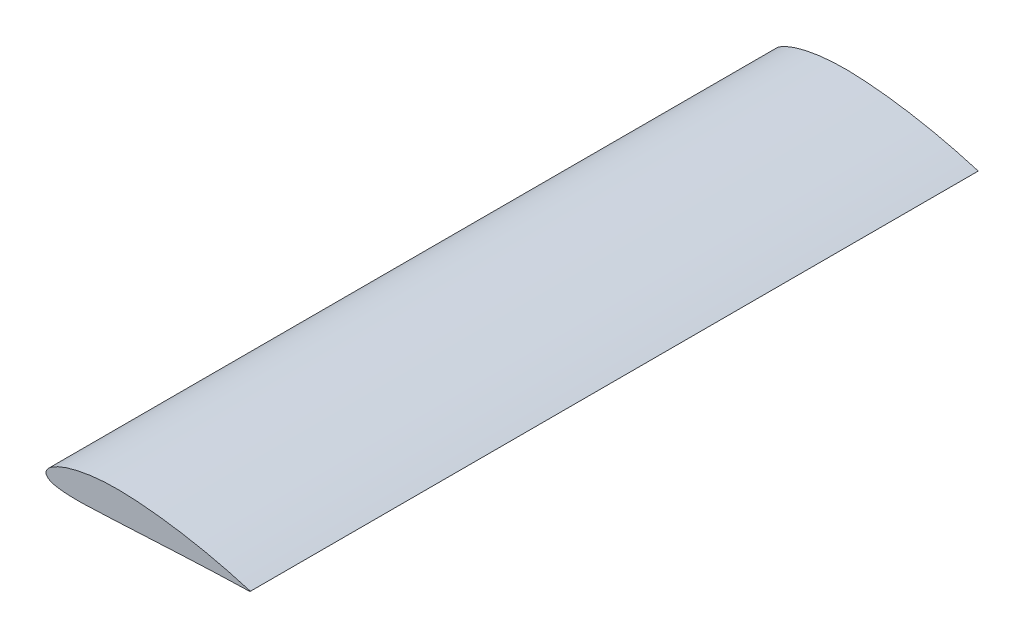
SolidWorks part; units mm, degrees
ref_plane "Front Plane" through (0, 0, 0) normal (1, 0, 0) x (0, 1, 0)
ref_plane "Top Plane" through (0, 0, 0) normal (0, 0, 1) x (0, 1, 0)
ref_plane "Right Plane" through (0, 0, 0) normal (0, 1, 0) x (-1, 0, 0)
curve "Curve1"
  spline degree 3 poles (140.0272, 0.204, 0) (139.9568, 0.2252, 0) (139.6757, 0.3101, 0) (139.0445, 0.4996, 0) (137.9962, 0.8116, 0) (136.5364, 1.24, 0) (134.6729, 1.777, 0) (132.4156, 2.4129, 0) (129.7768, 3.1359, 0) (126.7711, 3.9337, 0) (123.4152, 4.7928, 0) (119.7281, 5.6984, 0) (115.7307, 6.6363, 0) (111.4464, 7.5912, 0) (106.9, 8.5481, 0) (102.1186, 9.4924, 0) (97.1306, 10.4094, 0) (91.9664, 11.285, 0) (86.6574, 12.105, 0) (81.2364, 12.857, 0) (75.7371, 13.5278, 0) (70.1942, 14.1063, 0) (64.643, 14.582, 0) (59.1045, 14.945, 0) (53.595, 15.1934, 0) (48.1487, 15.2539, 0) (42.8195, 15.1314, 0) (37.6645, 14.8278, 0) (32.721, 14.3506, 0) (28.0244, 13.7113, 0) (23.608, 12.9241, 0) (19.5026, 12.0063, 0) (15.7359, 10.9777, 0) (12.3325, 9.8591, 0) (9.3132, 8.6734, 0) (6.6949, 7.4424, 0) (4.4906, 6.1877, 0) (2.7084, 4.928, 0) (1.3523, 3.6768, 0) (0.4223, 2.4391, 0) (-0.0704, 1.2019, 0) (-0.0774, -0.0155, 0) (0.3962, -1.1349, 0) (1.3132, -2.0898, 0) (2.6166, -2.8909, 0) (4.297, -3.5632, 0) (6.348, -4.1161, 0) (8.7591, -4.5545, 0) (11.516, -4.8827, 0) (14.6016, -5.1058, 0) (17.9973, -5.2305, 0) (21.6831, -5.2648, 0) (25.6381, -5.2189, 0) (29.8408, -5.1042, 0) (34.2692, -4.9332, 0) (38.9005, -4.7202, 0) (43.7112, -4.4799, 0) (48.6771, -4.2275, 0) (53.7919, -3.9752, 0) (59.0436, -3.7443, 0) (64.3998, -3.4808, 0) (69.8109, -3.2013, 0) (75.2301, -2.9143, 0) (80.6252, -2.6276, 0) (85.9637, -2.348, 0) (91.213, -2.0804, 0) (96.3409, -1.8293, 0) (101.3154, -1.5967, 0) (106.1052, -1.3844, 0) (110.68, -1.1929, 0) (115.0103, -1.0216, 0) (119.0681, -0.87, 0) (122.827, -0.7367, 0) (126.2621, -0.6209, 0) (129.3505, -0.521, 0) (132.0713, -0.4363, 0) (134.4061, -0.3656, 0) (136.3389, -0.3086, 0) (137.8565, -0.2644, 0) (138.948, -0.2331, 0) (139.6061, -0.2145, 0) (139.8994, -0.2061, 0) (139.9728, -0.204, 0) knots 0 0 0 0 0.000765 0.003057 0.00686 0.012149 0.018893 0.027046 0.036559 0.047372 0.059416 0.072616 0.086892 0.102153 0.118305 0.13525 0.152883 0.171093 0.18977 0.208797 0.228058 0.247433 0.266803 0.286048 0.305204 0.324202 0.342731 0.360679 0.377941 0.394414 0.410004 0.424621 0.438187 0.450631 0.461894 0.471932 0.480721 0.488263 0.494602 0.499855 0.504257 0.508229 0.5122 0.516589 0.52179 0.528018 0.535367 0.543866 0.553506 0.564253 0.57606 0.588869 0.602615 0.617228 0.632631 0.648744 0.665486 0.682768 0.700501 0.71879 0.737484 0.756321 0.775188 0.793972 0.812558 0.830833 0.848683 0.865998 0.882668 0.898589 0.913658 0.927778 0.940857 0.952809 0.963554 0.97302 0.981143 0.987868 0.993148 0.996946 0.999235 1 1 1 1
curve "Curve2"
  spline degree 3 poles (70, 0.091, 0) (68.8345, 0.4083, 0) (66.5092, 1.0413, 0) (61.851, 2.1922, 0) (56.0257, 3.4639, 0) (49.0189, 4.7174, 0) (42.0176, 5.745, 0) (35.0124, 6.4779, 0) (28.0078, 6.935, 0) (22.1603, 6.9396, 0) (17.4914, 6.6166, 0) (13.9849, 6.1912, 0) (10.4709, 5.5637, 0) (7.559, 4.8091, 0) (5.2255, 4.047, 0) (3.466, 3.3276, 0) (1.9647, 2.5495, 0) (0.6616, 1.6188, 0) (-0.4728, 0.1219, 0) (0.7517, -1.0228, 0) (2.001, -1.4722, 0) (3.489, -1.7755, 0) (5.2463, -1.9297, 0) (7.5824, -2.0389, 0) (10.5007, -2.0307, 0) (14.0015, -1.9327, 0) (17.4998, -1.7462, 0) (22.1665, -1.5279, 0) (27.9989, -1.2478, 0) (35.0002, -0.9848, 0) (41.9993, -0.6928, 0) (48.999, -0.4441, 0) (55.9993, -0.2611, 0) (61.8332, -0.1682, 0) (66.4999, -0.107, 0) (68.8333, -0.0963, 0) (70, -0.091, 0) knots 0 0 0 0 0.025305 0.050488 0.10052 0.150191 0.199587 0.24874 0.297716 0.346601 0.371103 0.395726 0.42057 0.445825 0.458702 0.47192 0.485786 0.493461 0.506863 0.516148 0.522766 0.535269 0.547551 0.559786 0.584229 0.608681 0.633151 0.657622 0.706558 0.755482 0.804406 0.85332 0.902221 0.951113 0.975557 1 1 1 1
sketch "Sketch3" plane through (0, 0, 0) normal (0, 0, 1) x (0, 1, 0)
  arc A0 (-0.2027, -140.0188) -> (0.204, -140.0272) centre (0.0018, -139.9661) ccw
  spline S0 degree 3 poles (1884.985, -806.4833) (-22.34, -198.466) (-8.6829, -169.6209) (0.4996, -139.0445) (0.8116, -137.9962) (1.24, -136.5364) (1.777, -134.6729) (2.4129, -132.4156) (3.1359, -129.7768) (3.9337, -126.7711) (4.7928, -123.4152) (5.6984, -119.7281) (6.6363, -115.7307) (7.5912, -111.4464) (8.5481, -106.9) (9.4924, -102.1186) (10.4094, -97.1306) (11.285, -91.9664) (12.105, -86.6574) (12.857, -81.2364) (13.5278, -75.7371) (14.1063, -70.1942) (14.582, -64.643) (14.945, -59.1045) (15.1934, -53.595) (15.2539, -48.1487) (15.1314, -42.8195) (14.8278, -37.6645) (14.3506, -32.721) (13.7113, -28.0244) (12.9241, -23.608) (12.0063, -19.5026) (10.9777, -15.7359) (9.8591, -12.3325) (8.6734, -9.3132) (7.4424, -6.6949) (6.1877, -4.4906) (4.928, -2.7084) (3.6768, -1.3523) (2.4391, -0.4223) (1.2019, 0.0704) (-0.0155, 0.0774) (-1.1349, -0.3962) (-2.0898, -1.3132) (-2.8909, -2.6166) (-3.5632, -4.297) (-4.1161, -6.348) (-4.5545, -8.7591) (-4.8827, -11.516) (-5.1058, -14.6016) (-5.2305, -17.9973) (-5.2648, -21.6831) (-5.2189, -25.6381) (-5.1042, -29.8408) (-4.9332, -34.2692) (-4.7202, -38.9005) (-4.4799, -43.7112) (-4.2275, -48.6771) (-3.9752, -53.7919) (-3.7443, -59.0436) (-3.4808, -64.3998) (-3.2013, -69.8109) (-2.9143, -75.2301) (-2.6276, -80.6252) (-2.348, -85.9637) (-2.0804, -91.213) (-1.8293, -96.3409) (-1.5967, -101.3154) (-1.3844, -106.1052) (-1.1929, -110.68) (-1.0216, -115.0103) (-0.87, -119.0681) (-0.7367, -122.827) (-0.6209, -126.2621) (-0.521, -129.3505) (-0.4363, -132.0713) (-0.3656, -134.4061) (-0.3086, -136.3389) (-0.2644, -137.8565) (-0.2331, -138.948) (1.2999, -193.0557) (5.588, -246.7199) (-1986.0508, -357.0454) knots -0.325451 -0.325451 -0.325451 -0.325451 0.000765 0.003057 0.00686 0.012149 0.018893 0.027046 0.036559 0.047372 0.059416 0.072616 0.086892 0.102153 0.118305 0.13525 0.152883 0.171093 0.18977 0.208797 0.228058 0.247433 0.266803 0.286048 0.305204 0.324202 0.342731 0.360679 0.377941 0.394414 0.410004 0.424621 0.438187 0.450631 0.461894 0.471932 0.480721 0.488263 0.494602 0.499855 0.504257 0.508229 0.5122 0.516589 0.52179 0.528018 0.535367 0.543866 0.553506 0.564253 0.57606 0.588869 0.602615 0.617228 0.632631 0.648744 0.665486 0.682768 0.700501 0.71879 0.737484 0.756321 0.775188 0.793972 0.812558 0.830833 0.848683 0.865998 0.882668 0.898589 0.913658 0.927778 0.940857 0.952809 0.963554 0.97302 0.981143 0.987868 0.993148 0.996946 0.999235 1.556579 1.556579 1.556579 1.556579 only from (0.204, -140.0272) to (-0.204, -139.9728) construction
  spline S1 degree 3 poles (0.204, -140.0272) (0.2252, -139.9568) (0.3101, -139.6757) (0.4996, -139.0445) (0.8116, -137.9962) (1.24, -136.5364) (1.777, -134.6729) (2.4129, -132.4156) (3.1359, -129.7768) (3.9337, -126.7711) (4.7928, -123.4152) (5.6984, -119.7281) (6.6363, -115.7307) (7.5912, -111.4464) (8.5481, -106.9) (9.4924, -102.1186) (10.4094, -97.1306) (11.285, -91.9664) (12.105, -86.6574) (12.857, -81.2364) (13.5278, -75.7371) (14.1063, -70.1942) (14.582, -64.643) (14.945, -59.1045) (15.1934, -53.595) (15.2539, -48.1487) (15.1314, -42.8195) (14.8278, -37.6645) (14.3506, -32.721) (13.7113, -28.0244) (12.9241, -23.608) (12.0063, -19.5026) (10.9777, -15.7359) (9.8591, -12.3325) (8.6734, -9.3132) (7.4424, -6.6949) (6.1877, -4.4906) (4.928, -2.7084) (3.6768, -1.3523) (2.4391, -0.4223) (1.2019, 0.0704) (-0.0155, 0.0774) (-1.1349, -0.3962) (-2.0898, -1.3132) (-2.8909, -2.6166) (-3.5632, -4.297) (-4.1161, -6.348) (-4.5545, -8.7591) (-4.8827, -11.516) (-5.1058, -14.6016) (-5.2305, -17.9973) (-5.2648, -21.6831) (-5.2189, -25.6381) (-5.1042, -29.8408) (-4.9332, -34.2692) (-4.7202, -38.9005) (-4.4799, -43.7112) (-4.2275, -48.6771) (-3.9752, -53.7919) (-3.7443, -59.0436) (-3.4808, -64.3998) (-3.2013, -69.8109) (-2.9143, -75.2301) (-2.6276, -80.6252) (-2.348, -85.9637) (-2.0804, -91.213) (-1.8293, -96.3409) (-1.5967, -101.3154) (-1.3844, -106.1052) (-1.1929, -110.68) (-1.0216, -115.0103) (-0.87, -119.0681) (-0.7367, -122.827) (-0.6209, -126.2621) (-0.521, -129.3505) (-0.4363, -132.0713) (-0.3656, -134.4061) (-0.3086, -136.3389) (-0.2644, -137.8565) (-0.2331, -138.948) (-0.214, -139.6214) (-0.2052, -139.93) (-0.2027, -140.0188) knots 0 0 0 0 0.000765 0.003057 0.00686 0.012149 0.018893 0.027046 0.036559 0.047372 0.059416 0.072616 0.086892 0.102153 0.118305 0.13525 0.152883 0.171093 0.18977 0.208797 0.228058 0.247433 0.266803 0.286048 0.305204 0.324202 0.342731 0.360679 0.377941 0.394414 0.410004 0.424621 0.438187 0.450631 0.461894 0.471932 0.480721 0.488263 0.494602 0.499855 0.504257 0.508229 0.5122 0.516589 0.52179 0.528018 0.535367 0.543866 0.553506 0.564253 0.57606 0.588869 0.602615 0.617228 0.632631 0.648744 0.665486 0.682768 0.700501 0.71879 0.737484 0.756321 0.775188 0.793972 0.812558 0.830833 0.848683 0.865998 0.882668 0.898589 0.913658 0.927778 0.940857 0.952809 0.963554 0.97302 0.981143 0.987868 0.993148 0.996946 0.999235 1.00016 1.00016 1.00016 1.00016
  point P0 (0, 0)
ref_plane "Plane2" through (0, 0, 500) normal (0, 0, 1) x (0, 1, 0)
ref_plane "Plane3" through (0, 0, 38.1) normal (0, 0, 1) x (0, 1, 0)
sketch "Sketch4" plane through (0, 0, 500) normal (0, 0, 1) x (0, 1, 0)
  arc A1 (-0.2027, -140.0188) -> (0.204, -140.0272) centre (0.0018, -139.9661) ccw
  spline S0 degree 3 poles (1884.887, -806.452) (-22.3395, -198.4651) (-8.6827, -169.6204) (0.4996, -139.0445) (0.8116, -137.9962) (1.24, -136.5364) (1.777, -134.6729) (2.4129, -132.4156) (3.1359, -129.7768) (3.9337, -126.7711) (4.7928, -123.4152) (5.6984, -119.7281) (6.6363, -115.7307) (7.5912, -111.4464) (8.5481, -106.9) (9.4924, -102.1186) (10.4094, -97.1306) (11.285, -91.9664) (12.105, -86.6574) (12.857, -81.2364) (13.5278, -75.7371) (14.1063, -70.1942) (14.582, -64.643) (14.945, -59.1045) (15.1934, -53.595) (15.2539, -48.1487) (15.1314, -42.8195) (14.8278, -37.6645) (14.3506, -32.721) (13.7113, -28.0244) (12.9241, -23.608) (12.0063, -19.5026) (10.9777, -15.7359) (9.8591, -12.3325) (8.6734, -9.3132) (7.4424, -6.6949) (6.1877, -4.4906) (4.928, -2.7084) (3.6768, -1.3523) (2.4391, -0.4223) (1.2019, 0.0704) (-0.0155, 0.0774) (-1.1349, -0.3962) (-2.0898, -1.3132) (-2.8909, -2.6166) (-3.5632, -4.297) (-4.1161, -6.348) (-4.5545, -8.7591) (-4.8827, -11.516) (-5.1058, -14.6016) (-5.2305, -17.9973) (-5.2648, -21.6831) (-5.2189, -25.6381) (-5.1042, -29.8408) (-4.9332, -34.2692) (-4.7202, -38.9005) (-4.4799, -43.7112) (-4.2275, -48.6771) (-3.9752, -53.7919) (-3.7443, -59.0436) (-3.4808, -64.3998) (-3.2013, -69.8109) (-2.9143, -75.2301) (-2.6276, -80.6252) (-2.348, -85.9637) (-2.0804, -91.213) (-1.8293, -96.3409) (-1.5967, -101.3154) (-1.3844, -106.1052) (-1.1929, -110.68) (-1.0216, -115.0103) (-0.87, -119.0681) (-0.7367, -122.827) (-0.6209, -126.2621) (-0.521, -129.3505) (-0.4363, -132.0713) (-0.3656, -134.4061) (-0.3086, -136.3389) (-0.2644, -137.8565) (-0.2331, -138.948) (1.2999, -193.0558) (5.588, -246.72) (-1986.0588, -357.0458) knots -0.325446 -0.325446 -0.325446 -0.325446 0.000765 0.003057 0.00686 0.012149 0.018893 0.027046 0.036559 0.047372 0.059416 0.072616 0.086892 0.102153 0.118305 0.13525 0.152883 0.171093 0.18977 0.208797 0.228058 0.247433 0.266803 0.286048 0.305204 0.324202 0.342731 0.360679 0.377941 0.394414 0.410004 0.424621 0.438187 0.450631 0.461894 0.471932 0.480721 0.488263 0.494602 0.499855 0.504257 0.508229 0.5122 0.516589 0.52179 0.528018 0.535367 0.543866 0.553506 0.564253 0.57606 0.588869 0.602615 0.617228 0.632631 0.648744 0.665486 0.682768 0.700501 0.71879 0.737484 0.756321 0.775188 0.793972 0.812558 0.830833 0.848683 0.865998 0.882668 0.898589 0.913658 0.927778 0.940857 0.952809 0.963554 0.97302 0.981143 0.987868 0.993148 0.996946 0.999235 1.55658 1.55658 1.55658 1.55658 only from (0.204, -140.0272) to (-0.2027, -140.0188) construction
  spline S1 degree 3 poles (0.204, -140.0272) (0.2252, -139.9568) (0.3101, -139.6757) (0.4996, -139.0445) (0.8116, -137.9962) (1.24, -136.5364) (1.777, -134.6729) (2.4129, -132.4156) (3.1359, -129.7768) (3.9337, -126.7711) (4.7928, -123.4152) (5.6984, -119.7281) (6.6363, -115.7307) (7.5912, -111.4464) (8.5481, -106.9) (9.4924, -102.1186) (10.4094, -97.1306) (11.285, -91.9664) (12.105, -86.6574) (12.857, -81.2364) (13.5278, -75.7371) (14.1063, -70.1942) (14.582, -64.643) (14.945, -59.1045) (15.1934, -53.595) (15.2539, -48.1487) (15.1314, -42.8195) (14.8278, -37.6645) (14.3506, -32.721) (13.7113, -28.0244) (12.9241, -23.608) (12.0063, -19.5026) (10.9777, -15.7359) (9.8591, -12.3325) (8.6734, -9.3132) (7.4424, -6.6949) (6.1877, -4.4906) (4.928, -2.7084) (3.6768, -1.3523) (2.4391, -0.4223) (1.2019, 0.0704) (-0.0155, 0.0774) (-1.1349, -0.3962) (-2.0898, -1.3132) (-2.8909, -2.6166) (-3.5632, -4.297) (-4.1161, -6.348) (-4.5545, -8.7591) (-4.8827, -11.516) (-5.1058, -14.6016) (-5.2305, -17.9973) (-5.2648, -21.6831) (-5.2189, -25.6381) (-5.1042, -29.8408) (-4.9332, -34.2692) (-4.7202, -38.9005) (-4.4799, -43.7112) (-4.2275, -48.6771) (-3.9752, -53.7919) (-3.7443, -59.0436) (-3.4808, -64.3998) (-3.2013, -69.8109) (-2.9143, -75.2301) (-2.6276, -80.6252) (-2.348, -85.9637) (-2.0804, -91.213) (-1.8293, -96.3409) (-1.5967, -101.3154) (-1.3844, -106.1052) (-1.1929, -110.68) (-1.0216, -115.0103) (-0.87, -119.0681) (-0.7367, -122.827) (-0.6209, -126.2621) (-0.521, -129.3505) (-0.4363, -132.0713) (-0.3656, -134.4061) (-0.3086, -136.3389) (-0.2644, -137.8565) (-0.2331, -138.948) (-0.214, -139.6214) (-0.2052, -139.93) (-0.2027, -140.0188) knots 0 0 0 0 0.000765 0.003057 0.00686 0.012149 0.018893 0.027046 0.036559 0.047372 0.059416 0.072616 0.086892 0.102153 0.118305 0.13525 0.152883 0.171093 0.18977 0.208797 0.228058 0.247433 0.266803 0.286048 0.305204 0.324202 0.342731 0.360679 0.377941 0.394414 0.410004 0.424621 0.438187 0.450631 0.461894 0.471932 0.480721 0.488263 0.494602 0.499855 0.504257 0.508229 0.5122 0.516589 0.52179 0.528018 0.535367 0.543866 0.553506 0.564253 0.57606 0.588869 0.602615 0.617228 0.632631 0.648744 0.665486 0.682768 0.700501 0.71879 0.737484 0.756321 0.775188 0.793972 0.812558 0.830833 0.848683 0.865998 0.882668 0.898589 0.913658 0.927778 0.940857 0.952809 0.963554 0.97302 0.981143 0.987868 0.993148 0.996946 0.999235 1.00016 1.00016 1.00016 1.00016
loft "Loft1" add profiles "Sketch3", "Sketch4"
